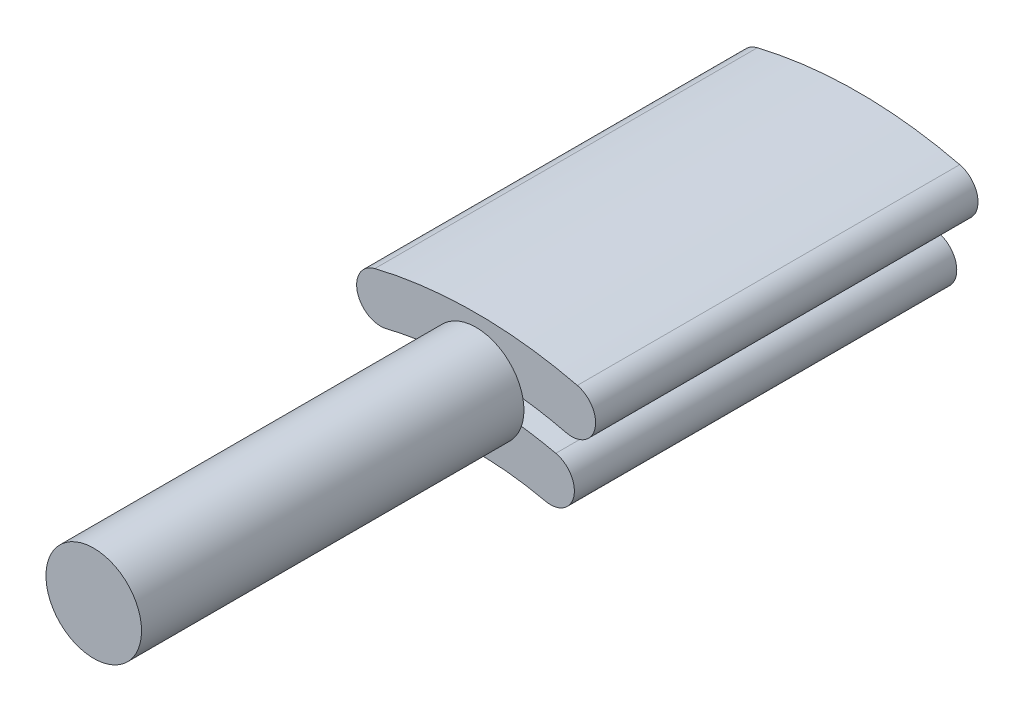
SolidWorks part; units mm, degrees
ref_plane "Front Plane" through (0, 0, 0) normal (0, 0, 1) x (1, 0, 0)
ref_plane "Top Plane" through (0, 0, 0) normal (0, 1, 0) x (1, 0, 0)
ref_plane "Right Plane" through (0, 0, 0) normal (1, 0, 0) x (0, 0, -1)
sketch "Sketch1" plane through (0, 0, 0) normal (0, 0, 1) x (1, 0, 0)
  line L0 (0, 57.15) -> (0, 0) construction
  line L1 (0, 0) -> (15.7859, 51.7126) construction
  line L2 (13.4471, 55.5455) -> (11.9529, 49.3738) construction
  line L3 (12.7, 52.4596) -> (15.7859, 51.7126) construction
  line L4 (10.5863, 46.3032) -> (9.171, 40.113) construction
  line L5 (9.8786, 43.2081) -> (12.9738, 42.5005) construction
  arc A0 (-11.9529, 49.3738) -> (11.9529, 49.3738) centre (0, 0) cw
  arc A1 (-13.4471, 55.5455) -> (13.4471, 55.5455) centre (0, 0) cw
  arc A2 (13.4471, 55.5455) -> (11.9529, 49.3738) centre (12.7, 52.4596) cw
  arc A3 (-13.4471, 55.5455) -> (-11.9529, 49.3738) centre (-12.7, 52.4596) ccw
  arc A4 (-10.5863, 46.3032) -> (10.5863, 46.3032) centre (0, 0) cw
  arc A5 (-9.171, 40.113) -> (9.171, 40.113) centre (0, 0) cw
  arc A6 (-10.5863, 46.3032) -> (-9.171, 40.113) centre (-9.8786, 43.2081) ccw
  arc A7 (10.5863, 46.3032) -> (9.171, 40.113) centre (9.8786, 43.2081) cw
  point P7 (0, 50.8)
  point P14 (5.9403, 18.7094)
  point P15 (0, 47.498)
  point P17 (0, 41.148)
  point P20 (0, 0)
  dimension "D2" = 50.8
  dimension "D3" = 3.175
  dimension "D4" = 3.302
  dimension "D1" = 25.4
extrude "Boss-Extrude1" add sketch "Sketch1" against normal blind 50.8
sketch "Sketch2" plane through (0, 0, 0) normal (0, 0, 1) x (1, 0, 0)
  line L0 (0, 50.8) -> (0, 47.498) construction
  circle A0 centre (0, 49.149) radius 6.35
  arc A1 (11.9529, 49.3738) -> (-11.9529, 49.3738) centre (0, 0) ccw construction
  arc A2 (10.5863, 46.3032) -> (-10.5863, 46.3032) centre (0, 0) ccw construction
  point P10 (4.6381, 23.5321)
  point P11 (0, 49.149)
  dimension "D1" = 12.7
extrude "Boss-Extrude2" add sketch "Sketch2" along normal blind 50.8
